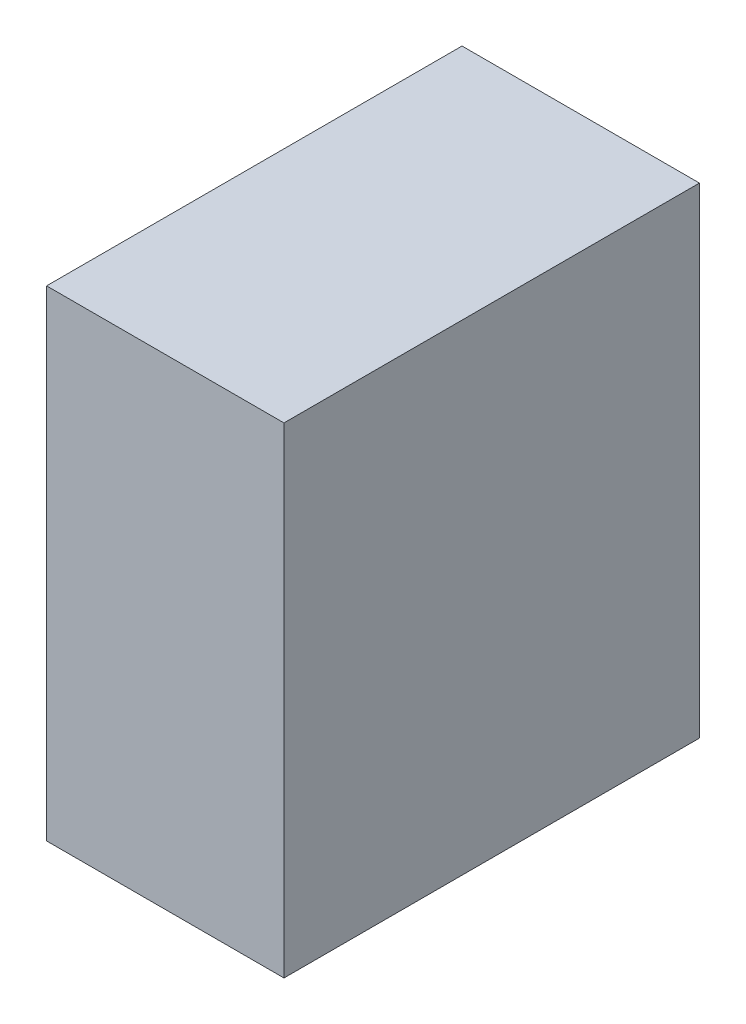
SolidWorks part; units mm, degrees
ref_plane "Front Plane" through (0, 0, 0) normal (0, 0, 1) x (1, 0, 0)
ref_plane "Top Plane" through (0, 0, 0) normal (0, 1, 0) x (1, 0, 0)
ref_plane "Right Plane" through (0, 0, 0) normal (1, 0, 0) x (0, 0, -1)
sketch "Sketch1" plane through (0, 0, 0) normal (0, 1, 0) x (1, 0, 0)
  line L1 (0, 0) -> (20.32, 0)
  line L2 (0, 0) -> (0, 35.56)
  line L3 (0, 35.56) -> (20.32, 35.56)
  line L4 (20.32, 0) -> (20.32, 35.56)
  dimension "D1" = 20.32
  dimension "D2" = 35.56
extrude "Boss-Extrude1" add sketch "Sketch1" along normal blind 41.148
